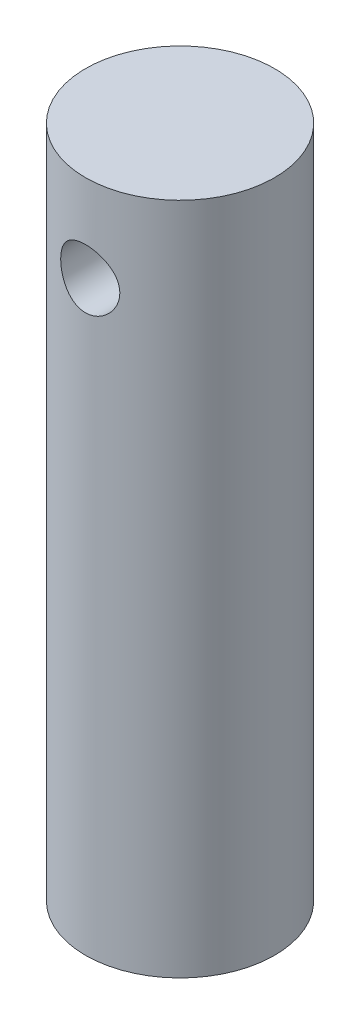
SolidWorks part; units mm, degrees
ref_plane "Front Plane" through (0, 0, 0) normal (0, 0, 1) x (1, 0, 0)
ref_plane "Top Plane" through (0, 0, 0) normal (0, 1, 0) x (1, 0, 0)
ref_plane "Right Plane" through (0, 0, 0) normal (1, 0, 0) x (0, 0, -1)
sketch "Sketch1" plane through (0, 0, 0) normal (0, 1, 0) x (1, 0, 0)
  circle A0 centre (0, 0) radius 10.16
  dimension "D1" = 20.32
extrude "Boss-Extrude1" add sketch "Sketch1" along normal blind 72.39
sketch "Sketch2" plane through (0, 0, 0) normal (0, 0, 1) x (1, 0, 0)
  line L0 (10.16, 72.39) -> (-10.16, 72.39) construction
  circle A0 centre (0, 62.992) radius 3.175
  point P2 (0, 0)
  dimension "D2" = 6.35
  dimension "D1" = 9.398
extrude "Cut-Extrude1" cut sketch "Sketch2" against normal through all and the other way through all
